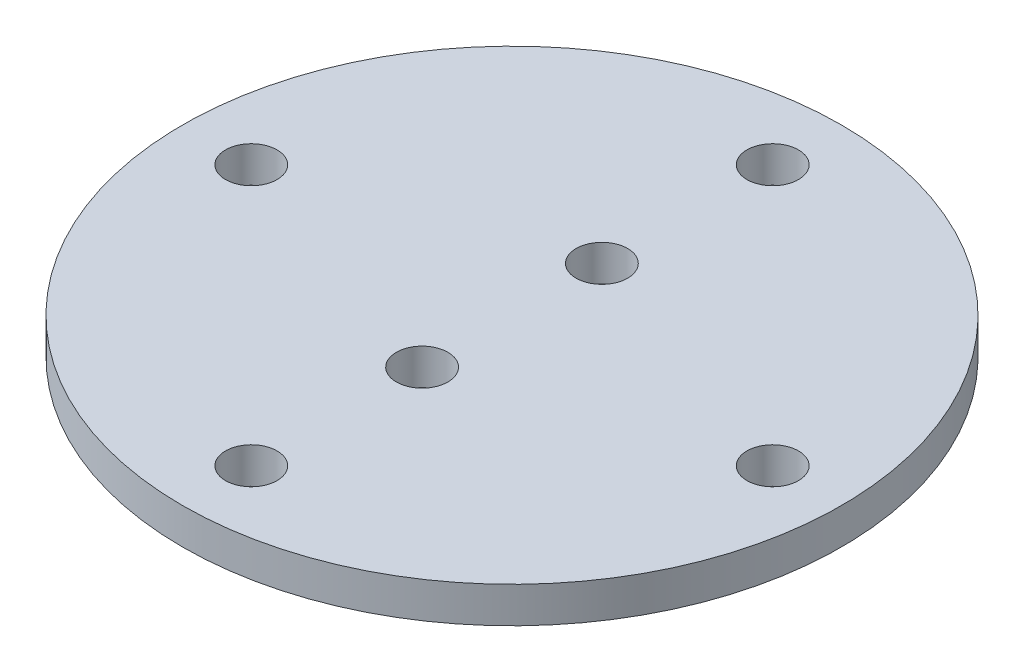
SolidWorks part; units mm, degrees
ref_plane "Front Plane" through (0, 0, 0) normal (0, 0, 1) x (1, 0, 0)
ref_plane "Top Plane" through (0, 0, 0) normal (0, 1, 0) x (1, 0, 0)
ref_plane "Right Plane" through (0, 0, 0) normal (1, 0, 0) x (0, 0, -1)
sketch "Sketch1" plane through (0, 0, 0) normal (0, 1, 0) x (1, 0, 0)
  circle A0 centre (0, -21.7549) radius 2.15 construction
  circle A1 centre (21.7549, 0) radius 2.15 construction
  circle A2 centre (0, 21.7549) radius 2.15 construction
  circle A3 centre (-21.7549, 0) radius 2.15 construction
  circle A4 centre (0, -21.7549) radius 2.15
  circle A5 centre (21.7549, 0) radius 2.15
  circle A6 centre (0, 21.7549) radius 2.15
  circle A7 centre (-21.7549, 0) radius 2.15
  circle A8 centre (0, 0) radius 27.5
  circle A9 centre (0, 7.5) radius 2.15
  circle A10 centre (0, -7.5) radius 2.15
  dimension "D1" = 55
extrude "Boss-Extrude1" add sketch "Sketch1" along normal blind 3
